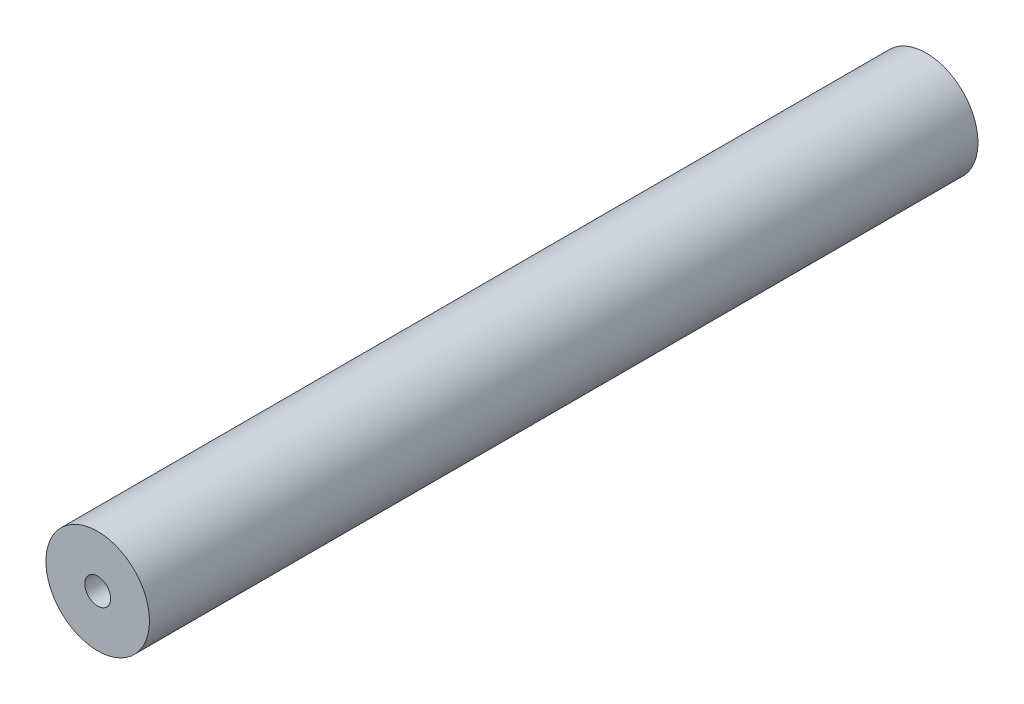
SolidWorks part; units mm, degrees
ref_plane "Front Plane" through (0, 0, 0) normal (0, 0, 1) x (1, 0, 0)
ref_plane "Top Plane" through (0, 0, 0) normal (0, 1, 0) x (1, 0, 0)
ref_plane "Right Plane" through (0, 0, 0) normal (1, 0, 0) x (0, 0, -1)
sketch "Sketch1" plane through (0, 0, 0) normal (0, 0, 1) x (1, 0, 0)
  circle A0 centre (0, 0) radius 20
  dimension "D1" = 40
extrude "Boss-Extrude1" add sketch "Sketch1" along normal blind 320
sketch "Sketch2" plane through (0, 0, 320) normal (0, 0, 1) x (1, 0, 0)
  circle A0 centre (0, 0) radius 5
  dimension "D1" = 10
extrude "Cut-Extrude1" cut sketch "Sketch2" against normal through all
